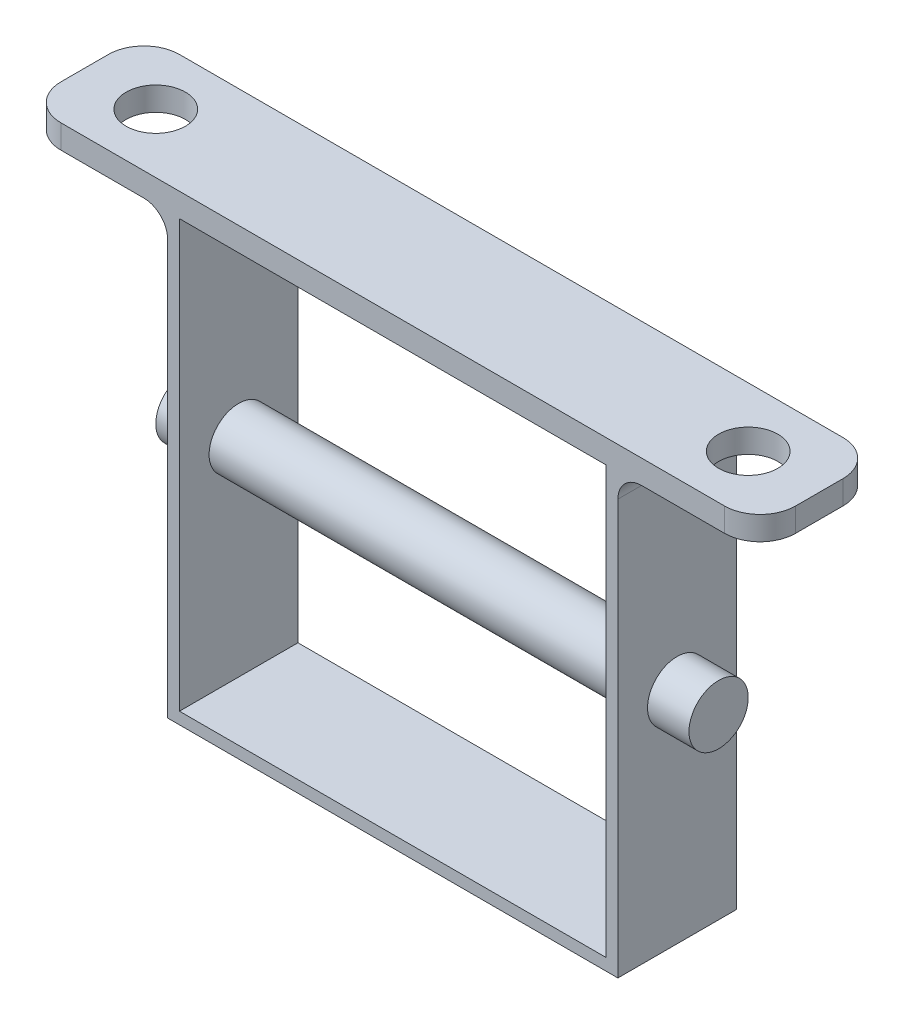
SolidWorks part; units mm, degrees
ref_plane "Front Plane" through (0, 0, 0) normal (0, 0, 1) x (1, 0, 0)
ref_plane "Top Plane" through (0, 0, 0) normal (0, 1, 0) x (1, 0, 0)
ref_plane "Right Plane" through (0, 0, 0) normal (1, 0, 0) x (0, 0, -1)
sketch "Sketch1" plane through (0, 0, 0) normal (0, 0, 1) x (1, 0, 0)
  line L1 (0, 0) -> (96.52, 0)
  line L2 (0, 0) -> (0, -96.52)
  line L3 (0, -96.52) -> (96.52, -96.52)
  line L4 (96.52, 0) -> (96.52, -96.52)
  line L5 (2.54, -2.54) -> (93.98, -2.54)
  line L6 (2.54, -2.54) -> (2.54, -93.98)
  line L7 (2.54, -93.98) -> (93.98, -93.98)
  line L8 (93.98, -2.54) -> (93.98, -93.98)
  dimension "D1" = 96.52
  dimension "D2" = 96.52
  dimension "D3" = 2.54
  dimension "D4" = 2.54
  dimension "D5" = 2.54
  dimension "D6" = 2.54
extrude "Boss-Extrude1" add sketch "Sketch1" along normal blind 25.4
sketch "Sketch3" plane through (0, 0, 0) normal (0, 1, 0) x (1, 0, 0)
  line L0 (0, -25.4) -> (0, 0) construction
  line L1 (-30.48, 0) -> (127, 0)
  line L2 (-30.48, 0) -> (-30.48, -25.4)
  line L3 (-30.48, -25.4) -> (127, -25.4)
  line L4 (127, 0) -> (127, -25.4)
  line L5 (96.52, -25.4) -> (96.52, 0) construction
  dimension "D1" = 25.4
  dimension "D2" = 30.48
  dimension "D3" = 30.48
extrude "Boss-Extrude2" add sketch "Sketch3" along normal mid plane 5.08
fillet "Fillet1" radius 5.08 2 edges at (0, -2.54, 12.7) (96.52, -2.54, 12.7)
sketch "Sketch4" plane through (0, -2.54, 0) normal (0, -1, 0) x (1, 0, 0)
  line L0 (127, 0) -> (101.6, 0) construction
  line L2 (127, 25.4) -> (127, 0) construction
  line L3 (48.26, 53.3687) -> (48.26, -28.7132) construction
  circle A0 centre (111.76, 12.7) radius 6.35
  circle A1 centre (-15.24, 12.7) radius 6.35
  dimension "D1" = 12.7
  dimension "D2" = 12.7
  dimension "D3" = 15.24
extrude "Cut-Extrude2" cut sketch "Sketch4" against normal through all
fillet "Fillet2" radius 7.62 4 edges at (-30.48, 0, 25.4) (-30.48, 0, 0) (127, 0, 0) (127, 0, 25.4)
ref_plane "Plane1" through (48.26, 0, 0) normal (1, 0, 0) x (0, 0, -1)
sketch "Sketch5" plane through (48.26, 0, 0) normal (1, 0, 0) x (0, 0, -1)
  line L0 (0, -7.62) -> (-25.4, -7.62) construction
  circle A0 centre (-12.7, -49.53) radius 6.35
  dimension "D1" = 12.7
  dimension "D2" = 41.91
extrude "Boss-Extrude4" add sketch "Sketch5" along normal mid plane 114.3
